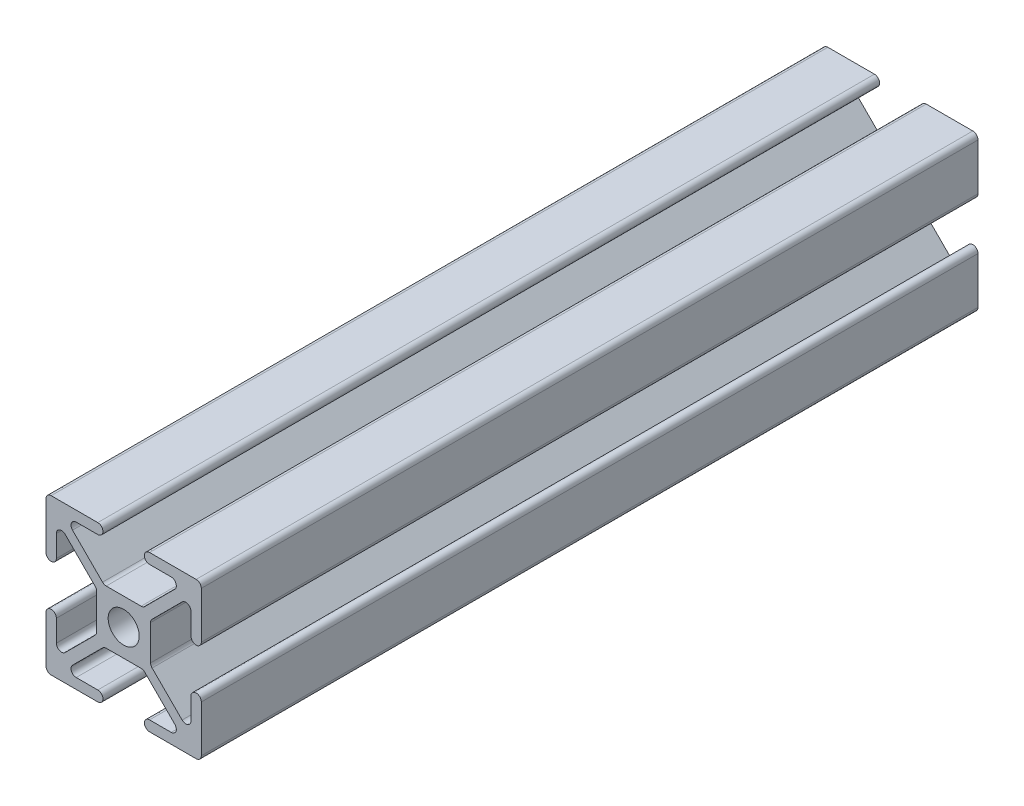
SolidWorks part; units mm, degrees
ref_plane "Alzado" through (0, 0, 0) normal (0, 0, 1) x (1, 0, 0)
ref_plane "Planta" through (0, 0, 0) normal (0, 1, 0) x (1, 0, 0)
ref_plane "Vista lateral" through (0, 0, 0) normal (1, 0, 0) x (0, 0, -1)
sketch "Croquis1" plane through (0, 0, 0) normal (0, 0, 1) x (1, 0, 0)
  line L1 (-14, 15) -> (14, 15)
  line L2 (-15, 14) -> (-15, -14)
  line L3 (-14, -15) -> (14, -15)
  line L4 (15, 14) -> (15, -14)
  line L5 (-15, 15) -> (15, -15) construction
  line L6 (-15, -15) -> (15, 15) construction
  arc A0 (-14, 15) -> (-15, 14) centre (-14, 14) ccw
  arc A1 (14, -15) -> (15, -14) centre (14, -14) ccw
  arc A2 (-14, -15) -> (-15, -14) centre (-14, -14) cw
  arc A3 (15, 14) -> (14, 15) centre (14, 14) ccw
  point P0 (0, 0)
  dimension "D3" = 1
  dimension "D4" = 1
  dimension "D1" = 30
  dimension "D2" = 30
extrude "Saliente-Extruir1" add sketch "Croquis1" against normal blind 150
sketch "Croquis2" plane through (0, 0, 0) normal (0, 0, 1) x (1, 0, 0)
  circle A0 centre (0, 0) radius 3
  dimension "D1" = 6
sketch "Croquis3" plane through (0, 0, 0) normal (0, 0, 1) x (1, 0, 0)
  line L0 (-15, 0) -> (15, 0) construction
  line L1 (4.0787, -5.4929) -> (9.8787, -11.2929)
  line L2 (-11.2929, 9.8787) -> (-5.4929, 4.0787)
  line L3 (-9.8787, 11.2929) -> (-4.0787, 5.4929)
  line L4 (-13, 9.1716) -> (-13, 5)
  line L5 (-15, 14) -> (-15, -14) construction
  line L6 (-5.2, 3.3716) -> (-5.2, -3.3716)
  line L7 (-9.1716, 13) -> (-5, 13)
  line L8 (9.8787, 11.2929) -> (4.0787, 5.4929)
  line L9 (11.2929, 9.8787) -> (5.4929, 4.0787)
  line L10 (-3.3716, 5.2) -> (3.3716, 5.2)
  line L11 (14, 15) -> (-14, 15) construction
  line L12 (13, 9.1716) -> (13, 5)
  line L13 (5.2, 3.3716) -> (5.2, -3.3716)
  line L14 (15, -14) -> (15, 14) construction
  line L15 (-9.1716, -13) -> (-5, -13)
  line L16 (-3.3716, -5.2) -> (3.3716, -5.2)
  line L17 (-14, -15) -> (14, -15) construction
  line L18 (-5.4929, -4.0787) -> (-11.2929, -9.8787)
  line L19 (5.4929, -4.0787) -> (11.2929, -9.8787)
  line L20 (-4.0787, -5.4929) -> (-9.8787, -11.2929)
  line L21 (5, -13) -> (9.1716, -13)
  line L22 (-13, -5) -> (-13, -9.1716)
  line L23 (13, -5) -> (13, -9.1716)
  line L24 (0, 15) -> (0, -5.2) construction
  line L34 (5, 13) -> (9.1716, 13)
  arc A0 (9.8787, 11.2929) -> (9.1716, 13) centre (9.1716, 12) ccw
  arc A1 (-9.8787, 11.2929) -> (-9.1716, 13) centre (-9.1716, 12) cw
  arc A2 (9.8787, 11.2929) -> (9.1716, 13) centre (9.1716, 12) ccw
  arc A3 (13, 9.1716) -> (11.2929, 9.8787) centre (12, 9.1716) ccw
  arc A4 (11.2929, -9.8787) -> (13, -9.1716) centre (12, -9.1716) ccw
  arc A5 (9.1716, -13) -> (9.8787, -11.2929) centre (9.1716, -12) ccw
  arc A6 (-9.1716, -13) -> (-9.8787, -11.2929) centre (-9.1716, -12) cw
  arc A7 (-11.2929, -9.8787) -> (-13, -9.1716) centre (-12, -9.1716) cw
  arc A8 (-13, 9.1716) -> (-11.2929, 9.8787) centre (-12, 9.1716) cw
  arc A9 (-4.0787, -5.4929) -> (-3.3716, -5.2) centre (-3.3716, -6.2) cw
  arc A10 (3.3716, -5.2) -> (4.0787, -5.4929) centre (3.3716, -6.2) cw
  arc A11 (5.4929, -4.0787) -> (5.2, -3.3716) centre (6.2, -3.3716) cw
  arc A12 (5.2, 3.3716) -> (5.4929, 4.0787) centre (6.2, 3.3716) cw
  arc A13 (3.3716, 5.2) -> (4.0787, 5.4929) centre (3.3716, 6.2) ccw
  arc A14 (-3.3716, 5.2) -> (-4.0787, 5.4929) centre (-3.3716, 6.2) cw
  arc A15 (-5.4929, -4.0787) -> (-5.2, -3.3716) centre (-6.2, -3.3716) ccw
  arc A16 (-5.2, 3.3716) -> (-5.4929, 4.0787) centre (-6.2, 3.3716) ccw
  circle A17 centre (-14, -5) radius 1
  circle A18 centre (-14, 5) radius 1
  circle A19 centre (-5, -14) radius 1
  circle A20 centre (5, -14) radius 1
  circle A21 centre (14, 5) radius 1
  circle A22 centre (14, -5) radius 1
  circle A23 centre (-5, 14) radius 1
  circle A24 centre (5, 14) radius 1
  point P20 (-11.5858, -13)
  point P30 (-13, -11.5858)
  point P43 (-3.7858, -5.2)
  point P50 (3.7858, -5.2)
  point P53 (5.2, -3.7858)
  point P62 (-5.2, -3.7858)
  line M2 (-15, 14) -> (-15, -14)
  line M4 (-14, -15) -> (14, -15)
  line M6 (15, -14) -> (15, 14)
  line M8 (14, 15) -> (-14, 15)
  dimension "D6" = 9.8
  dimension "D7" = 2
  dimension "D12" = 2
  dimension "D19" = 1
  dimension "D2" = 1
  dimension "D3" = 1
  dimension "D4" = 1
  dimension "D16" = 1
  dimension "D5" = 2
  dimension "D8" = 9.8
  dimension "D9" = 2
  dimension "D10" = 9.8
  dimension "D11" = 9.8
  dimension "D15" = 1
  dimension "D20" = 1
  dimension "D23" = 1
  dimension "D24" = 1
  dimension "D27" = 1
  dimension "D28" = 1
extrude "Cortar-Extruir1" cut sketch "Croquis2" against normal through all
extrude "Cortar-Extruir3" cut sketch "Croquis3" against normal through all contours A18 A17 L22 A7 L18 A15 L6 A16 L2 A8 L4 M2 | A24 A23 L7 A1 L3 A14 L10 A13 L8 A0 L34 M8 | A20 L21 A5 L1 A10 L16 A9 L20 A6 L15 A19 M4 | A22 A21 L12 A3 L9 A12 L13 A11 L19 A4 L23 M6
